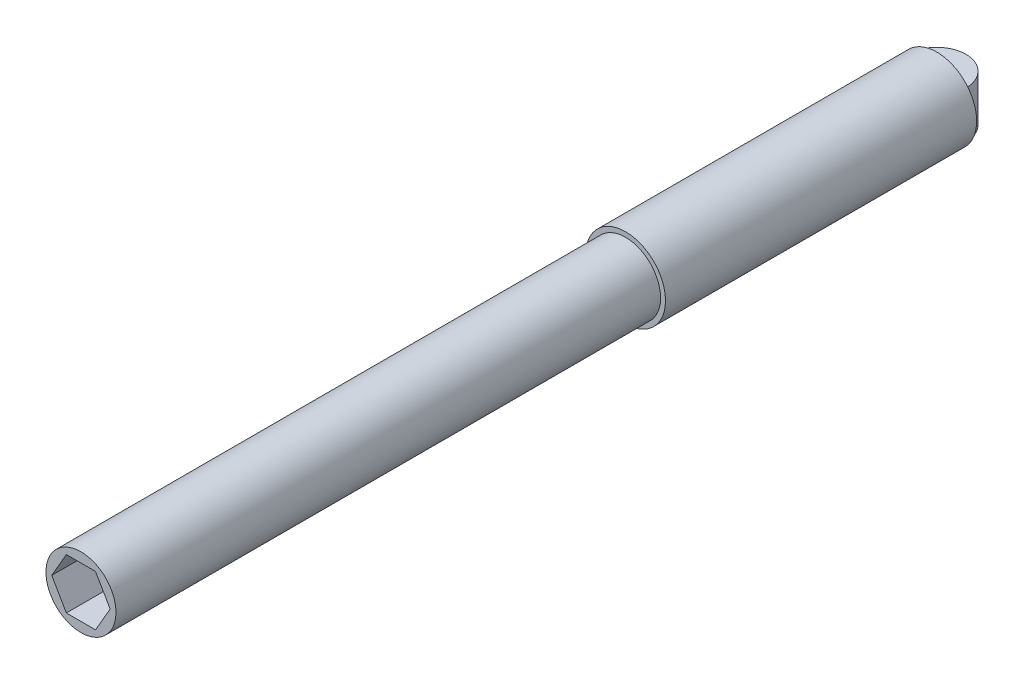
SolidWorks part; units mm, degrees
ref_plane "Front Plane" through (0, 0, 0) normal (0, 0, 1) x (1, 0, 0)
ref_plane "Top Plane" through (0, 0, 0) normal (0, 1, 0) x (1, 0, 0)
ref_plane "Right Plane" through (0, 0, 0) normal (1, 0, 0) x (0, 0, -1)
sketch "Sketch1" plane through (0, 0, 0) normal (0, 0, 1) x (1, 0, 0)
  circle A0 centre (0, 0) radius 1.025
  dimension "D1" = 2.05
extrude "Boss-Extrude1" add sketch "Sketch1" along normal blind 12
sketch "Sketch2" plane through (0, 0, 12) normal (0, 0, 1) x (1, 0, 0)
  line L0 (0, 0) -> (1.025, 0)
  line L2 (0.866, 0) -> (0.433, 0.75)
  line L3 (0.433, 0.75) -> (-0.433, 0.75)
  line L4 (-0.433, 0.75) -> (-0.866, 0)
  line L5 (-0.866, 0) -> (-0.433, -0.75)
  line L6 (-0.433, -0.75) -> (0.433, -0.75)
  line L7 (0.433, -0.75) -> (0.866, 0)
  circle A0 centre (0, 0) radius 1.025 construction
  circle A1 centre (0, 0) radius 0.75 construction
extrude "Cut-Extrude1" cut sketch "Sketch2" against normal blind 7
sketch "Sketch3" plane through (0, 0, 0) normal (0, 0, -1) x (-1, 0, 0)
  circle A0 centre (0, 0) radius 1.025
extrude "Boss-Extrude2" add sketch "Sketch3" along normal blind 4
sketch "Sketch4" plane through (0, 0, -4) normal (0, 0, -1) x (-1, 0, 0)
  line L0 (0, 0) -> (1.025, 0)
  circle A0 centre (0, 0) radius 1.025 construction
ref_plane "Plane3" through (0, 0, 0) normal (0, 1, 0) x (1, 0, 0)
sketch "Sketch5" plane through (0, 0, 0) normal (0, 1, 0) x (1, 0, 0)
  line L0 (1.025, 4) -> (-1.025, 4) construction
  line L1 (-1, 4) -> (1, 4)
  circle A0 centre (0, 4) radius 1
  dimension "D1" = 2
sketch "Sketch6" plane through (0, 0, 12) normal (0, 0, 1) x (1, 0, 0)
  line L1 (0.866, 0) -> (0.433, 0.75)
  line L2 (0.433, 0.75) -> (-0.433, 0.75)
  line L3 (-0.433, 0.75) -> (-0.866, 0)
  line L4 (-0.866, 0) -> (-0.433, -0.75)
  line L5 (-0.433, -0.75) -> (0.433, -0.75)
  line L6 (0.433, -0.75) -> (0.866, 0)
  circle A0 centre (0, 0) radius 0.75 construction
  circle A1 centre (0, 0) radius 1.025
extrude "Boss-Extrude5" add sketch "Sketch6" along normal blind 7
sketch "Sketch7" plane through (0, 0, -4) normal (0, 0, -1) x (-1, 0, 0)
  circle A0 centre (0, 0) radius 1.025
extrude "Boss-Extrude6" add sketch "Sketch7" along normal blind 2
sketch "Sketch8" plane through (0, 0, 0) normal (0, 1, 0) x (1, 0, 0)
  line L0 (1.025, 6) -> (-1.025, 6) construction
  line L1 (-0.75, 6) -> (0.75, 6)
  circle A0 centre (0, 6) radius 0.75
  dimension "D1" = 1.5
extrude "Boss-Extrude8" add sketch "Sketch8" along normal blind 0.6 and the other way blind 0.6 contours L1 A0
sketch "Sketch9" plane through (0, 0, 19) normal (0, 0, 1) x (1, 0, 0)
  circle A0 centre (0, 0) radius 1.025
extrude "Cut-Extrude3" cut sketch "Sketch9" against normal blind 17
sketch "Sketch10" plane through (0, 0, 2) normal (0, 0, 1) x (1, 0, 0)
  line L7 (0.7506, 0) -> (0.3753, 0.65)
  line L8 (0.3753, 0.65) -> (-0.3753, 0.65)
  line L9 (-0.3753, 0.65) -> (-0.7506, 0)
  line L10 (-0.7506, 0) -> (-0.3753, -0.65)
  line L11 (-0.3753, -0.65) -> (0.3753, -0.65)
  line L12 (0.3753, -0.65) -> (0.7506, 0)
  circle A0 centre (0, 0) radius 0.65 construction
  circle A1 centre (0, 0) radius 0.9
  dimension "D1" = 1.8
extrude "Boss-Extrude12" add sketch "Sketch10" along normal blind 14 contours L11 L12 L7 L8 L9 L10 | A1
sketch "Sketch12" plane through (0, 0, 16) normal (0, 0, 1) x (1, 0, 0)
  line L1 (0.7506, 0) -> (0.3753, 0.65)
  line L2 (0.3753, 0.65) -> (-0.3753, 0.65)
  line L3 (-0.3753, 0.65) -> (-0.7506, 0)
  line L4 (-0.7506, 0) -> (-0.3753, -0.65)
  line L5 (-0.3753, -0.65) -> (0.3753, -0.65)
  line L6 (0.3753, -0.65) -> (0.7506, 0)
  circle A0 centre (0, 0) radius 0.65 construction
